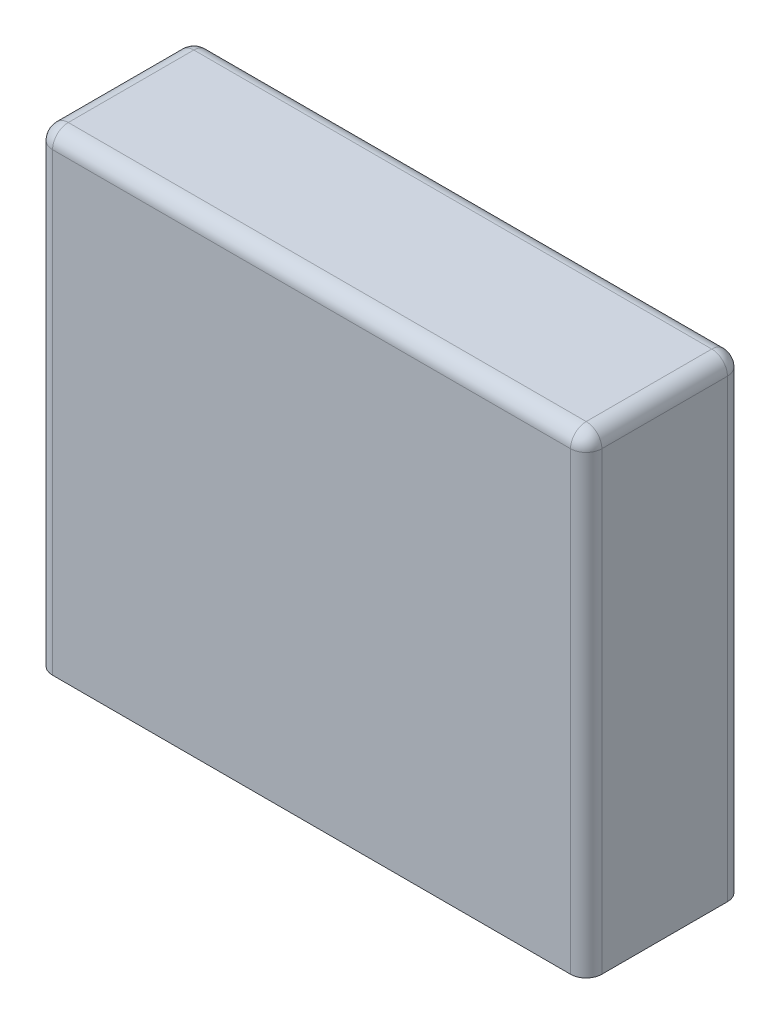
SolidWorks part; units mm, degrees
ref_plane "前基準面" through (0, 0, 0) normal (0, 0, 1) x (1, 0, 0)
ref_plane "上基準面" through (0, 0, 0) normal (0, 1, 0) x (1, 0, 0)
ref_plane "右基準面" through (0, 0, 0) normal (1, 0, 0) x (0, 0, -1)
sketch "草圖1" plane through (0, 0, 0) normal (0, 0, 1) x (1, 0, 0)
  line L1 (-3.5, 3) -> (3.5, 3)
  line L2 (-3.5, 3) -> (-3.5, -3)
  line L3 (-3.5, -3) -> (3.5, -3)
  line L4 (3.5, 3) -> (3.5, -3)
  line L5 (-3.5, 3) -> (3.5, -3) construction
  line L6 (-3.5, -3) -> (3.5, 3) construction
  point P0 (0, 0)
  dimension "D1" = 7
  dimension "D2" = 6
extrude "伸長1" add sketch "草圖1" along normal blind 2
fillet "圓角1" radius 0.2 8 edges at (3.5, 3, 1) (0, 3, 2) (-3.5, 3, 1) (0, 3, 0) (-3.5, 0, 2) (-3.5, 0, 0) (3.5, 0, 2) (3.5, 0, 0)
